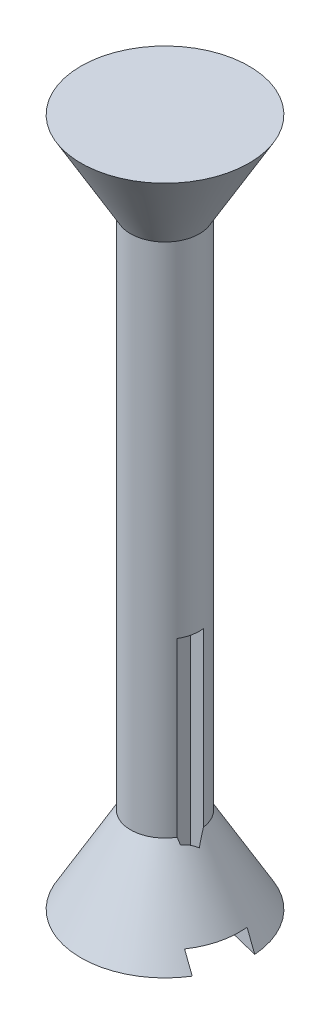
SolidWorks part; units mm, degrees
ref_plane "前视基准面" through (0, 0, 0) normal (0, 0, 1) x (1, 0, 0)
ref_plane "上视基准面" through (0, 0, 0) normal (0, 1, 0) x (1, 0, 0)
ref_plane "右视基准面" through (0, 0, 0) normal (1, 0, 0) x (0, 0, -1)
other "Configuration Table"
sketch "草图24" plane through (0, 0, 0) normal (0, 0, 1) x (1, 0, 0)
  line L0 (-45.7435, 338.2091) -> (-21.3098, 338.2091)
  line L1 (-21.3098, 338.2091) -> (-21.3098, 138.2091)
  line L2 (-21.3098, 138.2091) -> (-45.7435, 138.2091)
  line L3 (-45.7435, 138.2091) -> (-31.3098, 163.2091)
  line L4 (-31.3098, 163.2091) -> (-31.3098, 313.2091)
  line L5 (-31.3098, 313.2091) -> (-45.7435, 338.2091)
  point P2 (0, 0)
  point P7 (-21.3098, 338.2091)
  point P9 (0, 0)
  dimension "D1" = 10
  dimension "D2" = 200
  dimension "D3" = 150
  dimension "D4" = 25
  dimension "D5" = 60
  dimension "D6" = 60
revolve "旋转4" add sketch "草图24" angle 360 about L1
sketch "草图29" plane through (0, 338.2091, 0) normal (0, 1, 0) x (1, 0, 0)
  line L5 (3.0646, 1.7026) -> (-42.0858, 12.8594)
  line L6 (-0.5337, -12.8594) -> (-45.6841, -1.7026)
  line L7 (-42.0858, 12.8594) -> (-0.5337, -12.8594)
  line L8 (3.0646, 1.7026) -> (-45.6841, -1.7026)
  line L9 (-19.5106, 7.281) -> (-23.1089, -7.281)
  circle A0 centre (-21.3098, 0) radius 24.4338 construction
  arc A2 (-42.0858, 12.8594) -> (-45.6841, -1.7026) centre (-21.3098, 0) cw
  circle M5 centre (-21.3098, 0) radius 24.4338
  dimension "D3" = 46.5084
  dimension "D4" = 24.4338
  dimension "D1" = 15
  dimension "D2" = 46.5084
extrude "切除-拉伸3" cut sketch "草图29" against normal blind 5 from offset 195 contours L9 L5 L7 | L8 L7 M5 | L9 L8 L6 | L5 L9 L8 | L8 L7 M5 | L7 L9 L6 offset against normal yes
sketch "草图33" plane through (0, 143.2091, 0) normal (0, -1, 0) x (1, 0, 0)
  line L11 (-31.796, 3.4801) -> (-34.6828, -1.5199)
  line L12 (-34.6828, -1.5199) -> (-31.796, -6.5199)
  line L13 (-31.796, -6.5199) -> (-26.0225, -6.5199)
  line L14 (-26.0225, -6.5199) -> (-23.1358, -1.5199)
  line L15 (-23.1358, -1.5199) -> (-26.0225, 3.4801)
  line L16 (-26.0225, 3.4801) -> (-31.796, 3.4801)
  line L17 (-7.957, 1.6193) -> (-10.8437, 6.6193)
  line L18 (-10.8437, 6.6193) -> (-16.6172, 6.6193)
  line L19 (-16.6172, 6.6193) -> (-19.504, 1.6193)
  line L20 (-19.504, 1.6193) -> (-16.6172, -3.3807)
  line L21 (-16.6172, -3.3807) -> (-10.8437, -3.3807)
  line L22 (-10.8437, -3.3807) -> (-7.957, 1.6193)
  arc A0 (-42.0858, -12.8594) -> (-45.6841, 1.7026) centre (-21.3098, 0) ccw construction
  circle A2 centre (-28.9093, -1.5199) radius 1.6
  circle A3 centre (-13.7305, 1.6193) radius 1.6
  circle A4 centre (-28.9093, -1.5199) radius 5 construction
  circle A5 centre (-13.7305, 1.6193) radius 5 construction
  dimension "D1" = 3.2
  dimension "D2" = 3.2
  dimension "D3" = 15.5
  dimension "D4" = 7.75
  dimension "D5" = 5
  dimension "D6" = 5
extrude "切除-拉伸6" cut sketch "草图33" against normal blind 10 contours A2 | A3
sketch "草图35" plane through (0, 143.2091, 0) normal (0, -1, 0) x (1, 0, 0)
  line L1 (-24.9093, -1.5199) -> (-26.9093, 1.9442)
  line L2 (-26.9093, 1.9442) -> (-30.9093, 1.9442)
  line L3 (-30.9093, 1.9442) -> (-32.9093, -1.5199)
  line L4 (-32.9093, -1.5199) -> (-30.9093, -4.984)
  line L5 (-30.9093, -4.984) -> (-26.9093, -4.984)
  line L6 (-26.9093, -4.984) -> (-24.9093, -1.5199)
  line L7 (-9.7305, 1.6193) -> (-11.7305, 5.0834)
  line L8 (-11.7305, 5.0834) -> (-15.7305, 5.0834)
  line L9 (-15.7305, 5.0834) -> (-17.7305, 1.6193)
  line L10 (-17.7305, 1.6193) -> (-15.7305, -1.8448)
  line L11 (-15.7305, -1.8448) -> (-11.7305, -1.8448)
  line L12 (-11.7305, -1.8448) -> (-9.7305, 1.6193)
  circle A4 centre (-28.9093, -1.5199) radius 3.4641 construction
  circle A5 centre (-13.7305, 1.6193) radius 3.4641 construction
  dimension "D1" = 8
  dimension "D2" = 8
extrude "切除-拉伸21" cut sketch "草图35" against normal blind 60 from offset 10
